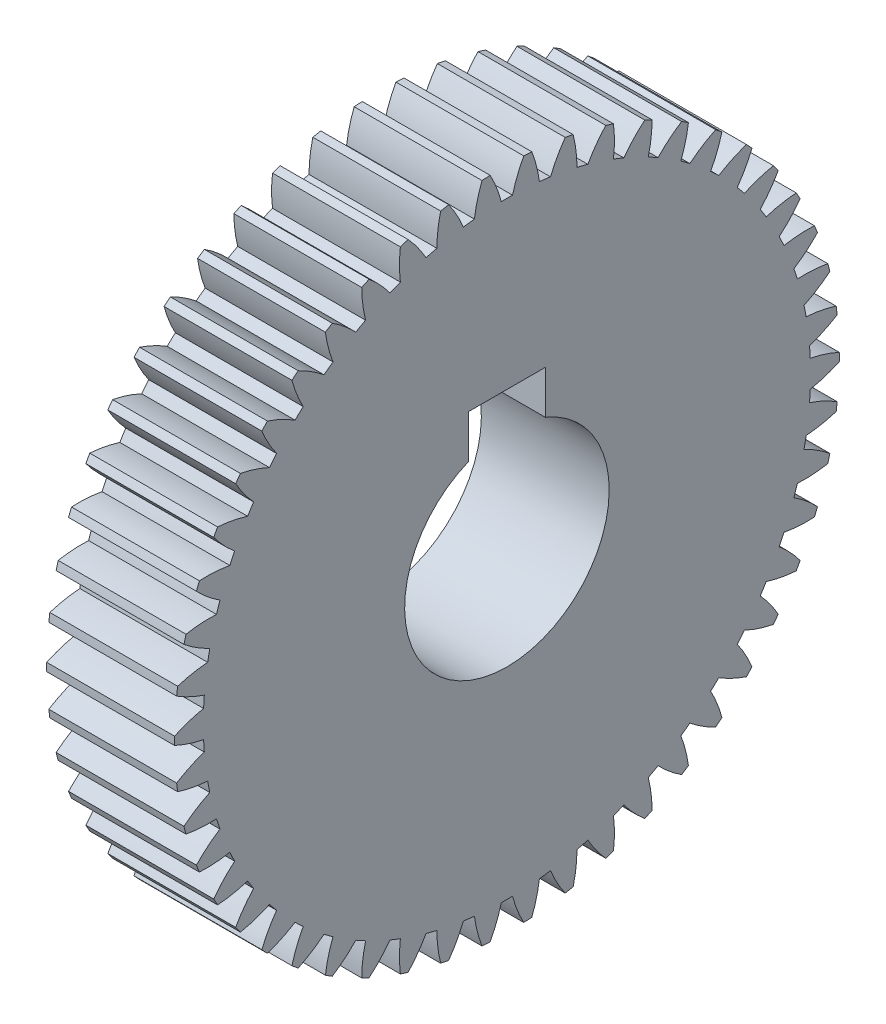
SolidWorks part; units mm, degrees
ref_plane "Plane1" through (0, 0, 0) normal (0, 0, 1) x (1, 0, 0)
ref_plane "Plane2" through (0, 0, 0) normal (0, 1, 0) x (1, 0, 0)
ref_plane "Plane3" through (0, 0, 0) normal (1, 0, 0) x (0, 0, -1)
other "Configuration Table"
sketch "HoldingSke" plane through (0, 0, 0) normal (0, 1, 0) x (1, 0, 0)
  line L0 (0, 0) -> (1.2856, -1.5321)
  line L1 (-15, 0) -> (100, 0) construction
  line L2 (0, 0) -> (-2.1039, 2.3779)
  line L3 (0, 0) -> (-11.863, 4.5341)
  line L4 (0, 0) -> (5.5511, 6.6156)
  line L5 (0, 0) -> (-46.8476, -17.4728)
  line L6 (0, 0) -> (-4.1448, -2.7965)
  line L7 (-2.1039, 2.3779) -> (8.6586, 51.2059)
  line L8 (-76.2, 54.61) -> (-74.8, 54.61)
  line L9 (-71.009, 38.7566) -> (-53.1078, 45.2721)
  line L10 (-76.2, 71.12) -> (104.1128, 71.12)
  line L11 (0, 0) -> (-5, 0)
  line L12 (-76.2, 101.6) -> (-76.181, 101.6)
  line L13 (24.9733, 27.94) -> (52.9518, 28.4284)
  line L14 (24.9733, 27.94) -> (24.9743, 27.94)
  line L15 (24.9733, 27.94) -> (100.4006, 29.5858)
  line L16 (-63.627, -0.5) -> (-12.827, -0.5)
  circle A0 centre (0, 0) radius 4
  circle A1 centre (0, 0) radius 11.874
  circle A2 centre (0, 0) radius 37.5
  circle A3 centre (0, 0) radius 4
  dimension "MHD" = 23.748
  dimension "Hub_dia" = 75
  dimension "Bore" = 8
  dimension "MBD" = 8
  dimension "Num_teeth" = 50
  dimension "Pitch" = 2
  dimension "Overall_len" = 50
  dimension "Show_teeth" = 50
  dimension "Thickness" = 5
  dimension "OAL" = 50.0001
  dimension "T_dim" = 1.4
  dimension "Ap" = 20
  dimension "H" = 19.05
  dimension "Pitch_radius" = 180.3128
  dimension "Width" = 5
  dimension "Backlash" = 0.019
  dimension "Addendum_fac" = 1
  dimension "Dedendum_fac" = 1.25
  dimension "Clearance_fac" = 0.25
  dimension "Dedendum_add" = 0.001
  dimension "Module" = 0.5
sketch "BasProSke" plane through (0, 0, 0) normal (0, 1, 0) x (1, 0, 0)
  line L0 (-10, 0) -> (60, 0) construction
  line L1 (0, 0) -> (0, 13)
  line L2 (0, 0) -> (5, 0)
  line L3 (5, 0) -> (5, 13)
  line L4 (5, 13) -> (0, 13)
  dimension "Thickness" = 5
  dimension "Diameter" = 26
revolve "Base-Revolve" add sketch "BasProSke" angle 360 about L0
sketch "TooCutSke" plane through (0, 0, 0) normal (1, 0, 0) x (0, 0, -1)
  line L1 (0, 0) -> (0, 107) construction
  line L2 (0, 0) -> (-0.4259, 12.4927) construction
  line L3 (0, 0) -> (-1.5691, 24.9404) construction
  line L4 (-0.4259, 12.4927) -> (-0.7846, 12.4702) construction
  arc A0 (0.2187, 11.872) -> (-0.2187, 11.872) centre (0, 0) ccw
  arc A1 (0.6715, 13.0081) -> (-0.6715, 13.0081) centre (0, 0) ccw
  circle A2 centre (0, 0) radius 12.5 construction
  circle A3 centre (0, 0) radius 11.7462 construction
  arc A4 (-0.2187, 11.872) -> (-0.6715, 13.0081) centre (-5.0549, 10.6028) ccw
  arc A5 (0.6715, 13.0081) -> (0.2187, 11.872) centre (5.0549, 10.6028) ccw
  dimension "Root_dia" = 23.748
  dimension "Overcut_dia" = 26.0508
  dimension "Pitch_dia" = 25
  dimension "Base_dia" = 23.4923
  dimension "Flank_rad" = 5
  dimension "Half_ang" = 3.6
  dimension "Half_CT" = 0.3594
extrude "ToothCut" cut sketch "TooCutSke" along normal through all
fillet "Breaks" [suppressed] radius 0.01
fillet "RootFillets" [suppressed] radius 0.126
pattern_circular "TeethCuts" count 50 every 7.2 about axis through (-10, 0, 0) along (1, 0, 0) of "ToothCut", "RootFillets", "Breaks"
sketch "HubNeaOneSke" plane through (0, 0, 0) normal (-1, 0, 0) x (0, 0, 1)
  circle A0 centre (0, 0) radius 11.874
  dimension "Diameter" = 23.748
extrude "HubNearOne" [suppressed] add sketch "HubNeaOneSke" along normal blind 45.0001
sketch "HubNeaBotSke" plane through (0, 0, 0) normal (-1, 0, 0) x (0, 0, 1)
  circle A0 centre (0, 0) radius 11.874
  dimension "Diameter" = 23.748
extrude "HubNearBoth" [suppressed] add sketch "HubNeaBotSke" along normal blind 22.5
ref_plane "FarPln" through (5, 0, 0) normal (1, 0, 0) x (0, 0, -1)
sketch "HubFarSke" plane through (5, 0, 0) normal (1, 0, 0) x (0, 0, -1)
  circle A0 centre (0, 0) radius 11.874
  dimension "Diameter" = 23.748
extrude "HubFar" [suppressed] add sketch "HubFarSke" along normal blind 22.5
sketch "BorSke" plane through (0, 0, 0) normal (1, 0, 0) x (0, 0, -1)
  circle A0 centre (0, 0) radius 4
  dimension "Diameter" = 8
extrude "Bore" cut sketch "BorSke" along normal mid plane 100.0001
sketch "KeySke" plane through (0, 0, 0) normal (1, 0, 0) x (0, 0, -1)
  line L0 (-1.5, 0) -> (-1.5, 5.4)
  line L1 (-1.5, 5.4) -> (1.5, 5.4)
  line L2 (1.5, 5.4) -> (1.5, 0)
  line L3 (0, 0) -> (0, 34) construction
  line L4 (-1.5, 0) -> (1.5, 0)
  dimension "Offset" = 5.4
  dimension "Width" = 3
extrude "Keyway" cut sketch "KeySke" along normal mid plane 100.0001
pattern_circular "Keyway2" [suppressed] count 2 every 90 about axis through (-10, 0, 0) along (1, 0, 0)
equation "' \"Module@HoldingSke\" = 6.35"
equation "' \"Num_teeth@HoldingSke\" = 12"
equation "' \"Ap@HoldingSke\" =  20"
equation "' \"Ap@HoldingSke\" = 20"
equation "' \"Width@HoldingSke\" = 0.5 * 25.4"
equation "' \"Hub_dia@HoldingSke\"= 1 * 25.4"
equation "' \"Hub_dia@HoldingSke\" = 1 * 25.4"
equation "' \"Overall_len@HoldingSke\" = 1.0 * 25.4"
equation "' \"Bore@HoldingSke\" = 0.75 * 25.4"
equation "' \"T_dim@HoldingSke\" = 0.1 * 25.4"
equation "' \"Width@KeySke\" = 0.25 * 25.4"
equation "' \"Show_teeth@HoldingSke\" = 13"
equation "' \"Backlash@HoldingSke\" = 0.009 * 25.4"
equation "' \"Addendum_fac@HoldingSke\" = 1.0"
equation "' \"Dedendum_fac@HoldingSke\" = 1.25"
equation "' \"Dedendum_add@HoldingSke\" = 0.00005 * 25.4"
equation "' \"Clearance_fac@HoldingSke\" = 0.25"
equation "\"Pitch@HoldingSke\" = 1 / \"Module@HoldingSke\""
equation "\"Overcut_dia@TooCutSke\" = (\"Num_teeth@HoldingSke\" + 2 * \"Addendum_fac@HoldingSke\") / \"Pitch@HoldingSke\" + 0.002 * 25.4"
equation "\"Pitch_dia@TooCutSke\" = \"Num_teeth@HoldingSke\" / \"Pitch@HoldingSke\""
equation "\"Base_dia@TooCutSke\" = \"Num_teeth@HoldingSke\" / \"Pitch@HoldingSke\" * cos((\"Ap@HoldingSke\"  * 3.14159265 / 180))"
equation "\"Root_dia@TooCutSke\" = (\"Num_teeth@HoldingSke\" + 2) / \"Pitch@HoldingSke\" - 2 * (\"Addendum_fac@HoldingSke\" + \"Dedendum_fac@HoldingSke\") / \"Pitch@HoldingSke\" - \"Dedendum_add@HoldingSke\" * 2"
equation "\"Half_ang@TooCutSke\" = 180 / \"Num_teeth@HoldingSke\""
equation "\"Half_CT@TooCutSke\" = \"Num_teeth@HoldingSke\" / \"Pitch@HoldingSke\" * sin((3.14159265 / 2 / \"Num_teeth@HoldingSke\")) / 2 - 7 * \"Backlash@HoldingSke\" / 4"
equation "\"Flank_rad@TooCutSke\" = \"Num_teeth@HoldingSke\" / \"Pitch@HoldingSke\" / 5"
equation "\"Radius@RootFillets\" = \"Clearance_fac@HoldingSke\" / \"Pitch@HoldingSke\" + \"Dedendum_add@HoldingSke\""
equation "\"Break_rad@Breaks\" = 0.02 / \"Pitch@HoldingSke\""
equation "\"Thickness@HoldingSke\" = \"Width@HoldingSke\""
equation "\"OAL@HoldingSke\" = \"Thickness@HoldingSke\""
equation "\"MHD@HoldingSke\" = (\"Num_teeth@HoldingSke\" + 2) / \"Pitch@HoldingSke\" - 2 * (\"Addendum_fac@HoldingSke\" + \"Dedendum_fac@HoldingSke\")  / \"Pitch@HoldingSke\" - \"Dedendum_add@HoldingSke\" * 2"
equation "\"MBD@HoldingSke\" = (\"Num_teeth@HoldingSke\" + 2) / \"Pitch@HoldingSke\" - 2 * (\"Addendum_fac@HoldingSke\" + \"Dedendum_fac@HoldingSke\")  / \"Pitch@HoldingSke\" - \"Dedendum_add@HoldingSke\" * 2 - 0.002 * 25.4"
equation "\"MHD@HoldingSke\" = ((sgn( \"MHD@HoldingSke\" - \"Hub_dia@HoldingSke\" )-1)*( \"MHD@HoldingSke\" - \"Hub_dia@HoldingSke\" ))/-2+ \"Hub_dia@HoldingSke\""
equation "\"MBD@HoldingSke\" = ((sgn( \"MBD@HoldingSke\" - \"Bore@HoldingSke\" )-1)*( \"MBD@HoldingSke\" - \"Bore@HoldingSke\" ))/-2+ \"Bore@HoldingSke\""
equation "\"OAL@HoldingSke\" = ((sgn( \"OAL@HoldingSke\" - \"Overall_len@HoldingSke\" )+1)*( \"OAL@HoldingSke\" - \"Overall_len@HoldingSke\" ))/2 + \"Overall_len@HoldingSke\" + 0.000002 * 25.4"
equation "\"Num_teeth@TeethCuts\" = int( \"Show_teeth@HoldingSke\" ) + 1"
equation "\"Num_teeth@TeethCuts\" = ((sgn( \"Num_teeth@TeethCuts\" - \"Num_teeth@HoldingSke\" )-1)*( \"Num_teeth@TeethCuts\" - \"Num_teeth@HoldingSke\" ))/-2+ \"Num_teeth@HoldingSke\""
equation "\"Num_teeth@TeethCuts\" = ((sgn( \"Num_teeth@TeethCuts\" - 2.0)+1)*( \"Num_teeth@TeethCuts\" - 2.0))/2 +2.0"
equation "\"Angle@TeethCuts\" = 360.0 / \"Num_teeth@HoldingSke\""
equation "\"Diameter@BasProSke\" = (\"Num_teeth@HoldingSke\" + 2 * \"Addendum_fac@HoldingSke\") / \"Pitch@HoldingSke\""
equation "\"Thickness@BasProSke\"  = \"Thickness@HoldingSke\""
equation "' \"Fillet_rad@BasProSke\" =  \"Thickness@HoldingSke\" * 0.05"
equation "' \"Fillet_rad@BasProSke\" = \"Thickness@HoldingSke\" * 0.05"
equation "\"MHD@HoldingSke\" = ((sgn( \"MHD@HoldingSke\" - \"Root_dia@TooCutSke\" )-1)*( \"MHD@HoldingSke\" - \"Root_dia@TooCutSke\" ))/-2+ \"Root_dia@TooCutSke\""
equation "\"Diameter@HubNeaOneSke\" = \"MHD@HoldingSke\""
equation "\"Length@HubNearOne\" = \"OAL@HoldingSke\" - \"Thickness@BasProSke\""
equation "\"Diameter@HubNeaBotSke\" = \"MHD@HoldingSke\""
equation "\"Length@HubNearBoth\" = ( \"OAL@HoldingSke\" - \"Thickness@BasProSke\" ) / 2.0"
equation "\"Thickness@FarPln\" = \"Thickness@BasProSke\""
equation "\"Diameter@HubFarSke\" = \"MHD@HoldingSke\""
equation "\"Length@HubFar\" = ( \"OAL@HoldingSke\" - \"Thickness@BasProSke\" ) / 2.0"
equation "\"Diameter@BorSke\" = \"MBD@HoldingSke\""
equation "\"D1@Bore\" = \"OAL@HoldingSke\" * 2.0"
equation "\"D1@Keyway\" = \"OAL@HoldingSke\" * 2.0"
equation "\"Offset@KeySke\" = \"T_dim@HoldingSke\" + \"MBD@HoldingSke\" / 2.0"
